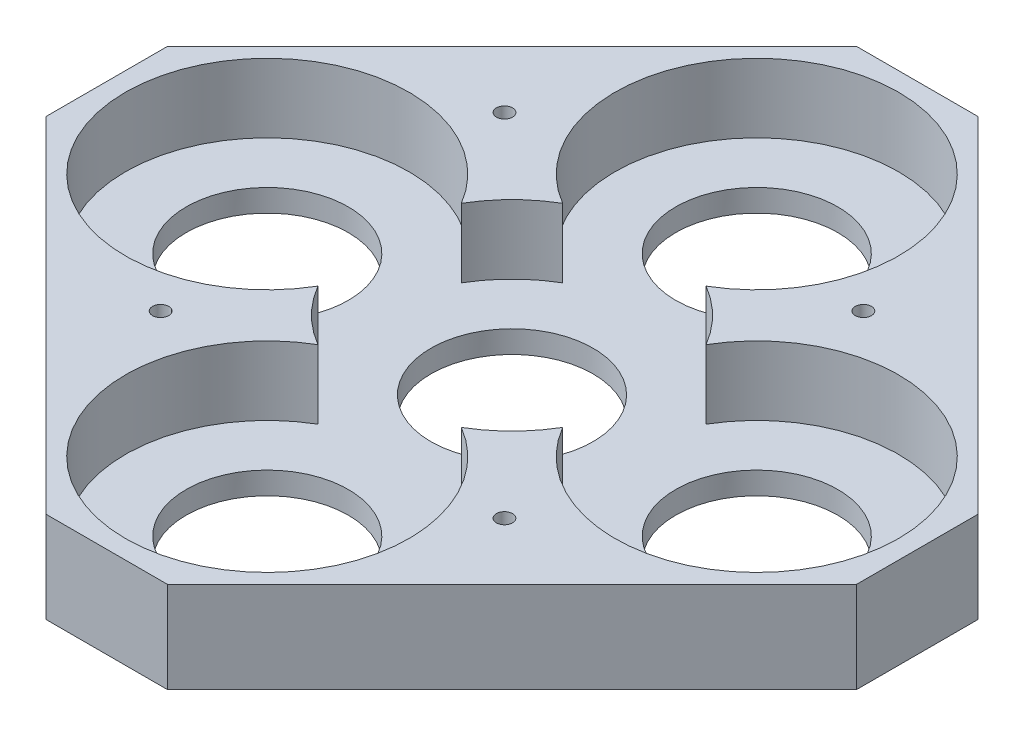
SolidWorks part; units mm, degrees
material "Pine"
ref_plane "Front Plane" through (0, 0, 0) normal (0, 0, 1) x (1, 0, 0)
ref_plane "Top Plane" through (0, 0, 0) normal (0, 1, 0) x (1, 0, 0)
ref_plane "Right Plane" through (0, 0, 0) normal (1, 0, 0) x (0, 0, -1)
sketch "Sketch1" plane through (0, 0, 0) normal (0, 1, 0) x (1, 0, 0)
  line L1 (0, 0) -> (254, 0)
  line L2 (0, 0) -> (0, 254)
  line L3 (0, 254) -> (254, 254)
  line L4 (254, 0) -> (254, 254)
  dimension "D1" = 254
  dimension "D2" = 254
extrude "Boss-Extrude1" add sketch "Sketch1" along normal blind 28.575
sketch "Sketch2" plane through (0, 28.575, 0) normal (0, 1, 0) x (1, 0, 0)
  line L0 (0, 0) -> (254, 0) construction
  arc A0 (149.4672, 88.646) -> (165.354, 104.5328) centre (127, 127) ccw
  arc A1 (104.5328, 88.646) -> (149.4672, 88.646) centre (127, 50.292) ccw
  arc A2 (88.646, 149.4672) -> (88.646, 104.5328) centre (50.292, 127) ccw
  arc A3 (149.4672, 88.646) -> (165.354, 104.5328) centre (127, 127) ccw
  arc A4 (149.4672, 165.354) -> (104.5328, 165.354) centre (127, 203.708) ccw
  arc A5 (149.4672, 88.646) -> (165.354, 104.5328) centre (127, 127) ccw
  arc A6 (165.354, 104.5328) -> (165.354, 149.4672) centre (203.708, 127) ccw
  arc A7 (149.4672, 88.646) -> (165.354, 104.5328) centre (127, 127) ccw
  arc A8 (88.646, 104.5328) -> (104.5328, 88.646) centre (127, 127) ccw
  arc A9 (88.646, 104.5328) -> (104.5328, 88.646) centre (127, 127) ccw
  arc A10 (88.646, 104.5328) -> (104.5328, 88.646) centre (127, 127) ccw
  arc A11 (88.646, 104.5328) -> (104.5328, 88.646) centre (127, 127) ccw
  arc A12 (104.5328, 165.354) -> (88.646, 149.4672) centre (127, 127) ccw
  arc A13 (104.5328, 165.354) -> (88.646, 149.4672) centre (127, 127) ccw
  arc A14 (104.5328, 165.354) -> (88.646, 149.4672) centre (127, 127) ccw
  arc A15 (104.5328, 165.354) -> (88.646, 149.4672) centre (127, 127) ccw
  arc A16 (165.354, 149.4672) -> (149.4672, 165.354) centre (127, 127) ccw
  arc A17 (165.354, 149.4672) -> (149.4672, 165.354) centre (127, 127) ccw
  arc A18 (165.354, 149.4672) -> (149.4672, 165.354) centre (127, 127) ccw
  arc A19 (165.354, 149.4672) -> (149.4672, 165.354) centre (127, 127) ccw
  point P18 (127, 127)
  dimension "D1" = 88.9
  dimension "D4" = 88.9
  dimension "D2" = 76.708
  dimension "D3" = 127
  dimension "D5" = 4
extrude "Cut-Extrude1" cut sketch "Sketch2" against normal blind 21.59 contours A6 A16 A4 A12 A2 A8 A1 A0
sketch "Sketch3" plane through (0, 6.985, 0) normal (0, 1, 0) x (1, 0, 0)
  circle A0 centre (127, 127) radius 25.4
  circle A1 centre (127, 50.292) radius 25.4
  circle A2 centre (50.292, 127) radius 25.4
  circle A3 centre (127, 203.708) radius 25.4
  circle A4 centre (203.708, 127) radius 25.4
  dimension "D1" = 50.8
extrude "Cut-Extrude2" cut sketch "Sketch3" against normal blind 16.51
fillet "Fillet1" radius 107.95 4 edges at (0, 14.2875, 0) (0, 14.2875, -254) (254, 14.2875, -254) (254, 14.2875, 0) profile chamfer
hole_wizard "#8 (0.199) Diameter Hole1" positions "Sketch9" profile "Sketch10" hole size "#8" standard "ANSI Inch" end condition through all
sketch "Sketch9" plane through (0, 28.575, 0) normal (0, 1, 0) x (1, 0, 0)
  line L0 (0, 107.95) -> (107.95, 0) construction
  line L1 (107.95, 254) -> (0, 146.05) construction
  line L2 (254, 146.05) -> (146.05, 254) construction
  line L3 (146.05, 0) -> (254, 107.95) construction
  point P0 (70.7526, 180.8815)
  point P2 (70.7526, 73.1185)
  point P4 (180.8815, 70.7526)
  point P6 (180.8815, 183.2474)
  dimension "D1" = 101.6
  dimension "D2" = 101.6
  dimension "D3" = 101.6
  dimension "D4" = 101.6
  dimension "D5" = 25.4
  dimension "D6" = 25.4
  dimension "D7" = 25.4
  dimension "D8" = 25.4
sketch "Sketch10" plane through (70.7526, 28.575, -180.8815) normal (1, 0, 0) x (0, 0, 1)
  line L0 (0, 0) -> (0, 28.575)
  line L1 (0, 28.575) -> (2.5273, 28.575)
  line L2 (2.5273, 28.575) -> (2.5273, 0)
  line L5 (2.5273, 0) -> (0, 0)
  line L11 (0, -6.35) -> (0, 107.95) construction
  dimension "Thru Hole Dia." = 5.0546
  dimension "Thru Hole Depth" = 28.575
